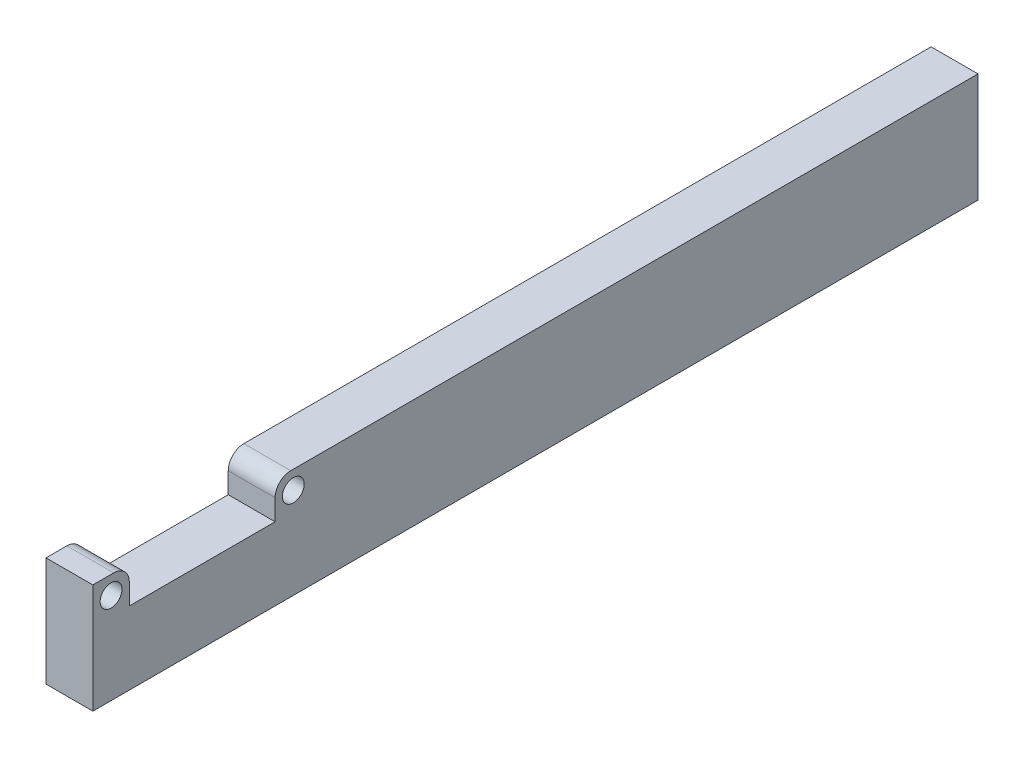
SolidWorks part; units mm, degrees
ref_plane "Front Plane" through (0, 0, 0) normal (0, 0, 1) x (1, 0, 0)
ref_plane "Top Plane" through (0, 0, 0) normal (0, 1, 0) x (1, 0, 0)
ref_plane "Right Plane" through (0, 0, 0) normal (1, 0, 0) x (0, 0, -1)
sketch "Sketch1" plane through (0, 0, 0) normal (1, 0, 0) x (0, 0, -1)
  line L1 (0, 0) -> (170, 0)
  line L2 (0, 0) -> (0, 21)
  line L3 (0, 21) -> (170, 21)
  line L4 (170, 0) -> (170, 21)
  dimension "D1" = 21
  dimension "D2" = 170
extrude "Boss-Extrude1" add sketch "Sketch1" along normal mid plane 9 contours L3 L4 L1 L2
sketch "Sketch3" plane through (0, 0, 0) normal (1, 0, 0) x (0, 0, -1)
  line L0 (0, 0) -> (0, 21) construction
  line L1 (0, 56) -> (42, 56)
  line L2 (0, 56) -> (0, 21)
  line L3 (7, 14) -> (35, 14)
  line L4 (42, 56) -> (42, 21)
  line L5 (0, 0) -> (170, 0) construction
  line L6 (0, 21) -> (7, 21)
  line L7 (7, 21) -> (7, 14)
  line L8 (35, 14) -> (35, 21)
  line L9 (35, 21) -> (42, 21)
  dimension "D1" = 0
  dimension "D2" = 42
  dimension "D4" = 14
  dimension "D5" = 7
  dimension "D6" = 7
  dimension "D7" = 7
extrude "Cut-Extrude2" cut sketch "Sketch3" against normal through all both and the other way through all
hole_wizard "M4 Clearance Hole1" positions "Sketch4" profile "Sketch5" hole size "M4" standard "ISO" end condition through all
sketch "Sketch4" plane through (4.5, 0, 0) normal (1, 0, 0) x (0, 0, -1)
  line L0 (3.5, 17.5) -> (38.5, 17.5) construction
  line L2 (21, 14) -> (21, 17.5) construction
  line L3 (7, 14) -> (35, 14) construction
  line L5 (7, 21) -> (7, 14) construction
  point P0 (3.5, 17.5)
  point P2 (38.5, 17.5)
  point P17 (7, 17.5)
  dimension "D1" = 35
sketch "Sketch5" plane through (4.5, 17.5, -3.5) normal (0, 1, 0) x (0, 0, -1)
  line L0 (0, 0) -> (0, 9)
  line L1 (0, 9) -> (2.1, 9)
  line L2 (2.1, 9) -> (2.1, 0)
  line L5 (2.1, 0) -> (0, 0)
  line L11 (0, -6.35) -> (0, 107.95) construction
  dimension "Thru Hole Dia." = 4.2
  dimension "Thru Hole Depth" = 9
fillet "Fillet1" radius 3 2 edges at (0, 21, -35) (0, 21, -7)
move or copy body "Body-Move/Copy1" [suppressed] bodies to move or copy 104
equation "\"D6@Sketch3\"=\"D5@Sketch3\""
equation "\"D7@Sketch3\"=\"D5@Sketch3\""
